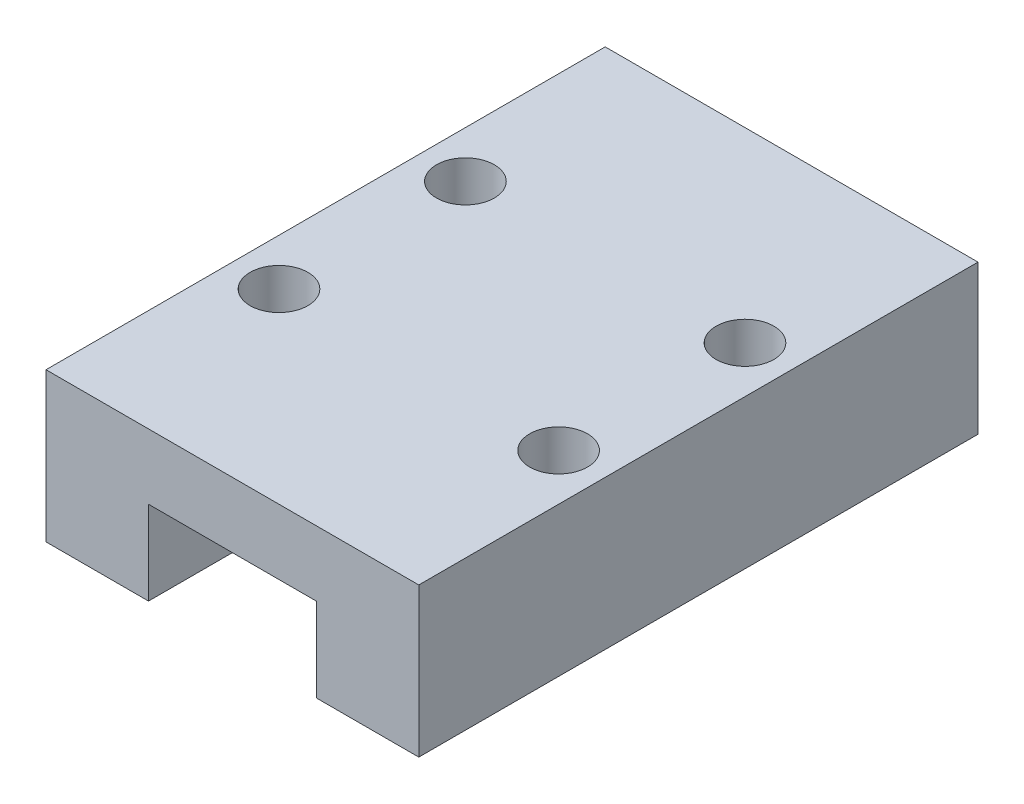
SolidWorks part; units mm, degrees
material "锻制不锈钢"
ref_plane "前视基准面" through (0, 0, 0) normal (0, 0, 1) x (1, 0, 0)
ref_plane "上视基准面" through (0, 0, 0) normal (0, 1, 0) x (1, 0, 0)
ref_plane "右视基准面" through (0, 0, 0) normal (1, 0, 0) x (0, 0, -1)
sketch "草图1" plane through (0, 0, 0) normal (0, 1, 0) x (1, 0, 0)
  line L1 (-10, 15) -> (10, 15)
  line L2 (-10, 15) -> (-10, -15)
  line L3 (-10, -15) -> (10, -15)
  line L4 (10, 15) -> (10, -15)
  line L5 (-10, 15) -> (10, -15) construction
  line L6 (-10, -15) -> (10, 15) construction
  point P0 (0, 0)
  dimension "D1" = 20
  dimension "D2" = 30
extrude "凸台-拉伸1" add sketch "草图1" along normal blind 3.5
ref_plane "基准面1" through (0, 0, 0) normal (0, -1, 0) x (-1, 0, 0)
sketch "草图2" plane through (0, 0, 0) normal (0, -1, 0) x (-1, 0, 0)
  line L0 (10, -15) -> (-10, -15) construction
  line L1 (-10, 15) -> (-4.5, 15)
  line L2 (-10, 15) -> (-10, -15)
  line L3 (-10, -15) -> (-4.5, -15)
  line L4 (-4.5, 15) -> (-4.5, -15)
  line L5 (0, 15) -> (0, -15) construction
  line L6 (-10, 15) -> (10, 15) construction
  line L7 (10, -15) -> (4.5, -15)
  line L8 (4.5, 15) -> (4.5, -15)
  line L9 (10, 15) -> (4.5, 15)
  line L10 (10, 15) -> (10, -15)
  dimension "D1" = 5.5
extrude "凸台-拉伸2" add sketch "草图2" along normal blind 4.5
ref_plane "基准面2" through (0, 3.5, 0) normal (0, 1, 0) x (1, 0, 0)
sketch "草图3" plane through (0, 3.5, 0) normal (0, 1, 0) x (1, 0, 0)
  line L1 (-7.5, 5) -> (7.5, 5) construction
  line L2 (-7.5, 5) -> (-7.5, -5) construction
  line L3 (-7.5, -5) -> (7.5, -5) construction
  line L4 (7.5, 5) -> (7.5, -5) construction
  line L5 (-7.5, 5) -> (7.5, -5) construction
  line L6 (-7.5, -5) -> (7.5, 5) construction
  circle A0 centre (-7.5, -5) radius 1.55
  circle A1 centre (-7.5, 5) radius 1.55
  circle A2 centre (7.5, 5) radius 1.55
  circle A3 centre (7.5, -5) radius 1.55
  point P0 (0, 0)
  dimension "D3" = 3.1
  dimension "D4" = 3.1
  dimension "D5" = 3.1
  dimension "D6" = 3.1
  dimension "D1" = 10
  dimension "D2" = 15
extrude "切除-拉伸1" cut sketch "草图3" against normal blind 8
